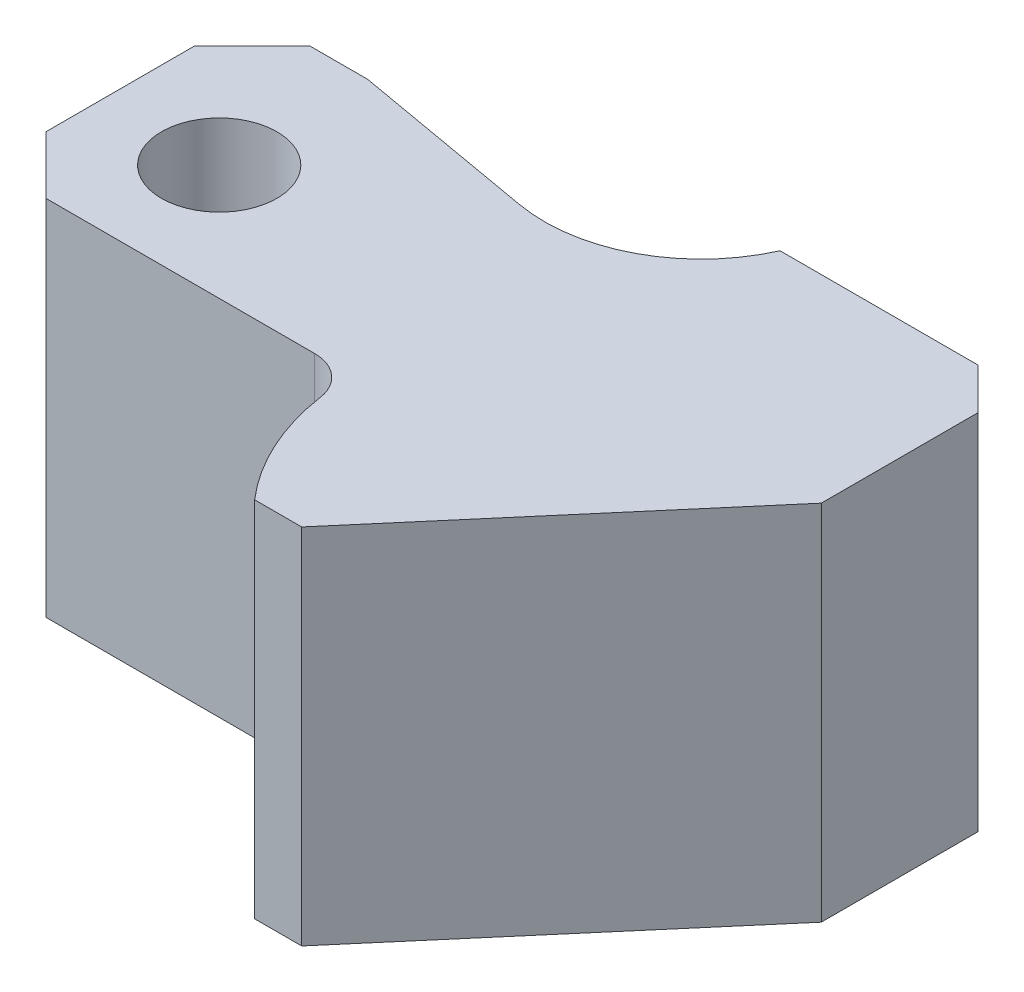
SolidWorks part; units mm, degrees
material "AISI 1020"
ref_plane "Front Plane" through (0, 0, 0) normal (0, 0, 1) x (1, 0, 0)
ref_plane "Top Plane" through (0, 0, 0) normal (0, 1, 0) x (1, 0, 0)
ref_plane "Right Plane" through (0, 0, 0) normal (1, 0, 0) x (0, 0, -1)
sketch "Sketch2" plane through (0, 0, 0) normal (0, 1, 0) x (1, 0, 0)
  line L0 (-8.0448, -3.2113) -> (-8.0448, 14.7887)
  line L1 (-1.0448, 21.7887) -> (5.9552, 21.7887)
  line L2 (5.9552, 21.7887) -> (28.3166, 17.8457)
  line L3 (48.9552, 28.7887) -> (72.9552, 28.7887)
  line L4 (77.9552, 23.7887) -> (77.9552, 4.7887)
  line L9 (-1.0448, -10.2113) -> (31.5307, -10.2113)
  line L10 (43.2522, -29.2113) -> (48.9552, -29.2113)
  line L11 (48.9552, -29.2113) -> (77.9552, 4.7887)
  line L12 (-8.0448, 14.7887) -> (-1.0448, 21.7887)
  line L13 (-1.0448, -10.2113) -> (-8.0448, -3.2113)
  line L14 (72.9552, 28.7887) -> (77.9552, 23.7887)
  arc A0 (28.3166, 17.8457) -> (48.9552, 28.7887) centre (31.6159, 36.5571) ccw
  arc A2 (31.5307, -10.2113) -> (36.4764, -14.4761) centre (31.5307, -15.2113) cw
  arc A3 (36.4764, -14.4761) -> (43.2522, -29.2113) centre (65.1611, -10.2113) ccw
  circle A4 centre (5.9552, 3.7887) radius 7
  point P0 (-8.0448, -10.2113)
  point P1 (-8.0448, 21.7887)
  point P8 (77.9552, 28.7887)
  dimension "D7" = 19
  dimension "D3" = 5
  dimension "D8" = 29
  dimension "D15" = 14
  dimension "D1" = 29
  dimension "D2" = 24
  dimension "D4" = 86
  dimension "D5" = 14
  dimension "D6" = 10
  dimension "D10" = 32
  dimension "D9" = 19
  dimension "D11" = 7
  dimension "D12" = 45
  dimension "D13" = 7
  dimension "D14" = 45
  dimension "D16" = 14
  dimension "D17" = 14
  dimension "D18" = 5
  dimension "D19" = 45
  dimension "D20" = 19
  dimension "D21" = 29
  dimension "D22" = 58
extrude "Boss-Extrude1" add sketch "Sketch2" along normal mid plane 44
equation "\"A\" = 86"
equation "\"B\" = 58"
equation "\"C\"= 44"
equation "\"D4@Sketch2\"=\"A\""
equation "\"D1@Boss-Extrude1\"=\"C\""
equation "\"D22@Sketch2\"=\"B\""
